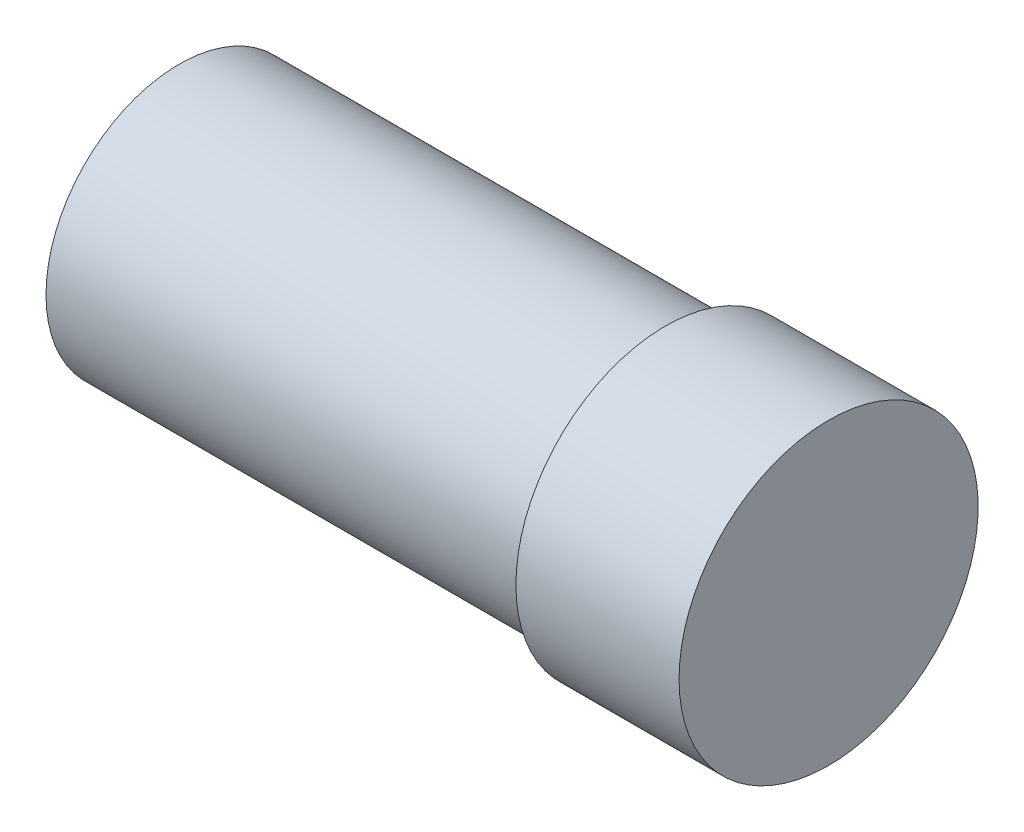
SolidWorks part; units mm, degrees
ref_plane "Front Plane" through (0, 0, 0) normal (0, 0, 1) x (1, 0, 0)
ref_plane "Top Plane" through (0, 0, 0) normal (0, 1, 0) x (1, 0, 0)
ref_plane "Right Plane" through (0, 0, 0) normal (1, 0, 0) x (0, 0, -1)
sketch "Sketch1" plane through (0, 0, 0) normal (0, 0, 1) x (1, 0, 0)
  line L0 (22.35, -12.25) -> (22.35, -13.75)
  line L1 (-22.35, 12.25) -> (22.35, 12.25)
  line L2 (-22.35, 12.25) -> (-22.35, -12.25)
  line L3 (-22.35, -12.25) -> (22.35, -12.25)
  line L5 (22.35, 13.75) -> (37.35, 13.75)
  line L6 (22.35, 13.75) -> (22.35, 12.25)
  line L7 (22.35, -13.75) -> (37.35, -13.75)
  line L8 (37.35, 13.75) -> (37.35, -13.75)
  line L9 (-22.35, 0) -> (1494.03, 0)
  point P9 (-22.35, 0)
  point P11 (0, 12.25)
  point P13 (37.35, 0)
  dimension "D1" = 59.7
  dimension "D2" = 24.5
  dimension "D3" = 27.5
  dimension "D4" = 15
revolve "Revolve1" add sketch "Sketch1" angle 360 about L9
